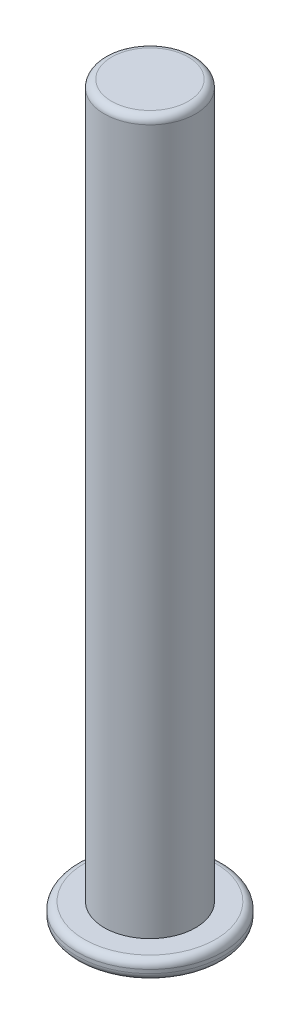
SolidWorks part; units mm, degrees
ref_plane "Front Plane" through (0, 0, 0) normal (0, 0, 1) x (1, 0, 0)
ref_plane "Top Plane" through (0, 0, 0) normal (0, 1, 0) x (1, 0, 0)
ref_plane "Right Plane" through (0, 0, 0) normal (1, 0, 0) x (0, 0, -1)
sketch "Sketch1" plane through (0, 0, 0) normal (0, 1, 0) x (1, 0, 0)
  circle A0 centre (0, 0) radius 8
extrude "Boss-Extrude1" add sketch "Sketch1" along normal blind 2
sketch "Sketch2" plane through (0, 0, 0) normal (0, 1, 0) x (1, 0, 0)
  circle A0 centre (0, 0) radius 5
extrude "Boss-Extrude2" add sketch "Sketch2" along normal blind 80
fillet "Fillet3" radius 0.8 3 edges at (0, 80, 5) (0, 2, 8) (0, 0, 8)
